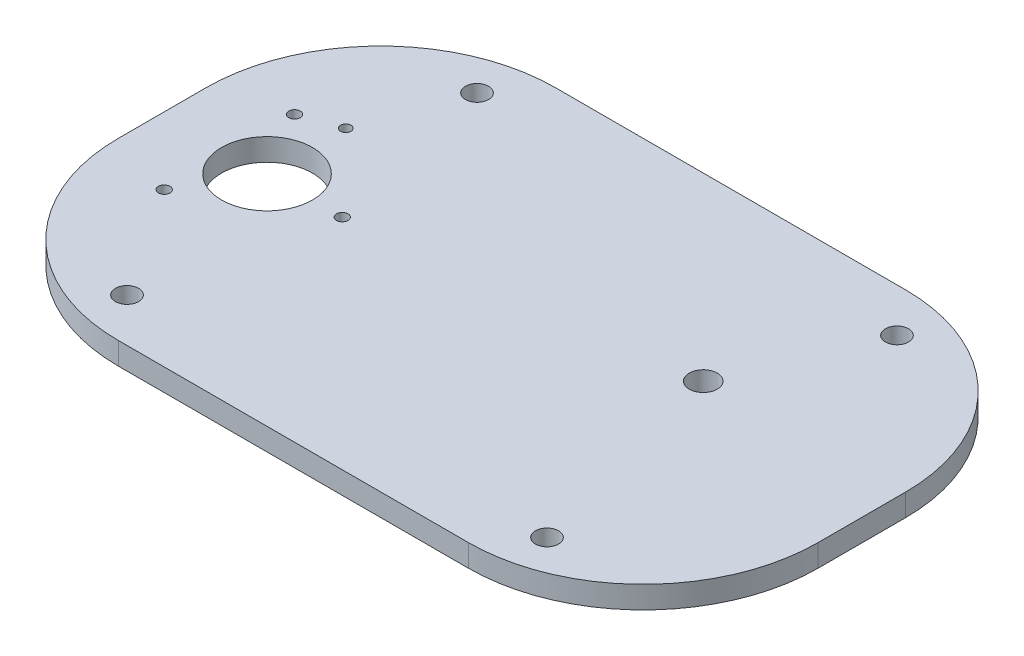
SolidWorks part; units mm, degrees
ref_plane "Front Plane" through (0, 0, 0) normal (0, 0, 1) x (1, 0, 0)
ref_plane "Top Plane" through (0, 0, 0) normal (0, 1, 0) x (1, 0, 0)
ref_plane "Right Plane" through (0, 0, 0) normal (1, 0, 0) x (0, 0, -1)
sketch "Sketch2" plane through (0, 0, 0) normal (0, 1, 0) x (1, 0, 0)
  line L1 (-100, -62.5) -> (100, -62.5)
  line L2 (-100, -62.5) -> (-100, 62.5)
  line L3 (-100, 62.5) -> (100, 62.5)
  line L4 (100, -62.5) -> (100, 62.5)
  line L5 (-100, -62.5) -> (100, 62.5) construction
  line L6 (-100, 62.5) -> (100, -62.5) construction
  arc A2 (-40.3, 0) -> (-99.7, 0) centre (-70, 0) ccw
  arc A3 (-99.7, 0) -> (-40.3, 0) centre (-70, 0) ccw
  arc A4 (-40.3, 0) -> (-99.7, 0) centre (-70, 0) ccw
  arc A5 (-99.7, 0) -> (-40.3, 0) centre (-70, 0) ccw
  arc A10 (-68.5, 22.5) -> (-71.5, 22.5) centre (-70, 22.5) ccw
  arc A11 (-71.5, 22.5) -> (-68.5, 22.5) centre (-70, 22.5) ccw
  arc A12 (-68.5, 22.5) -> (-71.5, 22.5) centre (-70, 22.5) ccw
  arc A13 (-71.5, 22.5) -> (-68.5, 22.5) centre (-70, 22.5) ccw
  arc A14 (-79.925, -17.1906) -> (-81.575, -20.0485) centre (-80.75, -18.6195) ccw
  arc A15 (-81.575, -20.0485) -> (-79.925, -17.1906) centre (-80.75, -18.6195) ccw
  arc A16 (-79.925, -17.1906) -> (-81.575, -20.0485) centre (-80.75, -18.6195) ccw
  arc A17 (-81.575, -20.0485) -> (-79.925, -17.1906) centre (-80.75, -18.6195) ccw
  arc A18 (-79.925, 17.1906) -> (-81.575, 20.0485) centre (-80.75, 18.6195) ccw
  arc A19 (-81.575, 20.0485) -> (-79.925, 17.1906) centre (-80.75, 18.6195) ccw
  arc A20 (-79.925, 17.1906) -> (-81.575, 20.0485) centre (-80.75, 18.6195) ccw
  arc A21 (-81.575, 20.0485) -> (-79.925, 17.1906) centre (-80.75, 18.6195) ccw
  arc A22 (-50.15, 0) -> (-46.85, 0) centre (-48.5, 0) ccw
  arc A23 (-46.85, 0) -> (-50.15, 0) centre (-48.5, 0) ccw
  arc A24 (-50.15, 0) -> (-46.85, 0) centre (-48.5, 0) ccw
  arc A25 (-46.85, 0) -> (-50.15, 0) centre (-48.5, 0) ccw
  arc A26 (-83, 0) -> (-57, 0) centre (-70, 0) ccw
  arc A27 (-57, 0) -> (-83, 0) centre (-70, 0) ccw
  arc A28 (-83, 0) -> (-57, 0) centre (-70, 0) ccw
  arc A29 (-57, 0) -> (-83, 0) centre (-70, 0) ccw
  circle A36 centre (43.6439, 11) radius 4
  circle A37 centre (43.6439, 11) radius 10.4365
  circle A38 centre (43.6439, 11) radius 10.4365
  point P0 (0, 0)
  dimension "D10" = 8
  dimension "D1" = 200
  dimension "D2" = 125
  dimension "D3" = 0
  dimension "D4" = 0
  dimension "D5" = 0
  dimension "D6" = 0
  dimension "D7" = 0
  dimension "D8" = 0
  dimension "D9" = 0
extrude "Boss-Extrude1" add sketch "Sketch2" along normal blind 6.35 contours A5 L2 L1 L4 L3 A4 | A4 A5 A29 A28 A25 A24 A21 A20 A17 A16 A13 A12 | A38 A36
fillet "Fillet1" radius 50 4 edges at (100, 3.175, 62.5) (100, 3.175, -62.5) (-100, 3.175, -62.5) (-100, 3.175, 62.5)
hole_wizard "M6 Clearance Hole1" positions "Sketch3" profile "Sketch4" hole size "M6" standard "ANSI Metric"
sketch "Sketch3" plane through (0, 6.35, 0) normal (0, 1, 0) x (1, 0, 0)
  line L1 (-60, -50) -> (60, -50)
  line L2 (-60, -50) -> (-60, 50)
  line L3 (-60, 50) -> (60, 50)
  line L4 (60, -50) -> (60, 50)
  line L5 (-60, -50) -> (60, 50) construction
  line L6 (-60, 50) -> (60, -50) construction
  point P2 (60, 50)
  point P111 (-60, -50)
  point P112 (-60, 50)
  point P113 (60, -50)
  dimension "D1" = 120
  dimension "D2" = 100
  dimension "D3" = 60
  dimension "D4" = 50
sketch "Sketch4" plane through (60, 6.35, -50) normal (1, 0, 0) x (0, 0, 1)
  line L0 (0, 0) -> (0, 16.9828)
  line L1 (0, 16.9828) -> (3.3, 15)
  line L2 (3.3, 15) -> (3.3, 0)
  line L5 (3.3, 0) -> (0, 0)
  line L10 (0, 16.9828) -> (-3.3, 15) construction
  line L11 (0, -6.35) -> (0, 107.95) construction
  dimension "Hole Dia." = 6.6
  dimension "Hole Depth" = 15
  dimension "Drill Angle" = 118
